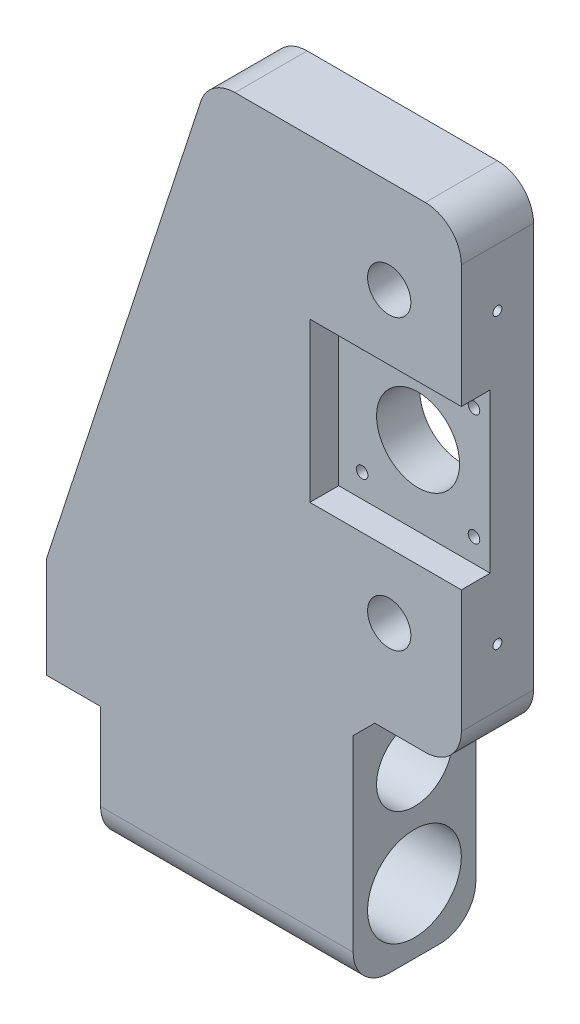
SolidWorks part; units mm, degrees
ref_plane "Front Plane" through (0, 0, 0) normal (0, 0, 1) x (1, 0, 0)
ref_plane "Top Plane" through (0, 0, 0) normal (0, 1, 0) x (1, 0, 0)
ref_plane "Right Plane" through (0, 0, 0) normal (1, 0, 0) x (0, 0, -1)
sketch "Sketch1" plane through (0, 0, 0) normal (0, 0, 1) x (1, 0, 0)
  line L0 (0, 0) -> (70, 0)
  line L1 (70, 0) -> (70, 62)
  line L2 (76, 68) -> (90, 68)
  line L3 (100, 78) -> (100, 190)
  line L4 (90, 200) -> (37.2574, 200)
  line L5 (27.7501, 193.1002) -> (-15, 62)
  line L6 (-15, 62) -> (-15, 34)
  line L7 (-15, 34) -> (0, 34)
  line L8 (0, 34) -> (0, 0)
  line L9 (70, 62) -> (76, 68)
  arc A0 (90, 68) -> (100, 78) centre (90, 78) ccw
  arc A1 (100, 190) -> (90, 200) centre (90, 190) ccw
  arc A2 (37.2574, 200) -> (27.7501, 193.1002) centre (37.2574, 190) ccw
  point P4 (70, 68)
  point P12 (100, 68)
  point P15 (100, 200)
  point P18 (30, 200)
  dimension "D8" = 10
  dimension "D1" = 70
  dimension "D2" = 200
  dimension "68" = 68
  dimension "D3" = 70
  dimension "D4" = 30
  dimension "D5" = 15
  dimension "D6" = 28
  dimension "D7" = 34
extrude "Boss-Extrude2" add sketch "Sketch1" along normal blind 34
sketch "Sketch3" plane through (0, 0, 0) normal (0, 0, -1) x (-1, 0, 0)
  line L6 (-100, 200) -> (80.4908, 200)
  line L7 (-100, 200) -> (-100, 62)
  line L8 (-100, 62) -> (80.4908, 62)
  line L9 (80.4908, 200) -> (80.4908, 62)
  line L11 (-90, 200) -> (-37.2574, 200) construction
  line L12 (-100, 78) -> (-100, 190) construction
  dimension "138" = 138
extrude "Cut-Extrude1" cut sketch "Sketch3" against normal blind 14
sketch "Sketch4" plane through (0, 0, 34) normal (0, 0, 1) x (1, 0, 0)
  line L1 (90, 200) -> (37.2574, 200) construction
  line L2 (100, 78) -> (100, 190) construction
  circle A0 centre (80, 134) radius 11.5
  circle A1 centre (95.5, 149.5) radius 1.6
  circle A2 centre (95.5, 118.5) radius 1.6
  circle A3 centre (64.5, 118.5) radius 1.6
  circle A4 centre (64.5, 149.5) radius 1.6
  circle A5 centre (80, 174) radius 6
  circle A6 centre (80, 94) radius 6
  point P17 (80, 134)
  point P19 (80, 134)
  point P20 (80, 134)
  point P21 (80, 134)
  dimension "D3" = 23
  dimension "11.58" = 11.5
  dimension "D5" = 3.2
  dimension "D7" = 12
  dimension "D10" = 15.5
  dimension "D1" = 66
  dimension "D2" = 20
  dimension "D4" = 15.5
  dimension "D8" = 40
  dimension "D9" = 80
  dimension "D6" = 4
extrude "Cut-Extrude3" cut sketch "Sketch4" against normal through all
sketch "Sketch5" plane through (0, 0, 34) normal (0, 0, 1) x (1, 0, 0)
  line L0 (100, 78) -> (100, 190) construction
  line L1 (58, 156) -> (100, 156)
  line L2 (58, 156) -> (58, 112)
  line L3 (58, 112) -> (100, 112)
  line L4 (100, 156) -> (100, 112)
  circle A0 centre (80, 134) radius 11.5 construction
  dimension "D1" = 44
  dimension "D2" = 42
  dimension "D3" = 22
extrude "Cut-Extrude4" cut sketch "Sketch5" against normal blind 8
sketch "Sketch8" plane through (100, 0, 0) normal (1, 0, 0) x (0, 0, -1)
  line L0 (-34, 200) -> (-14, 200) construction
  line L1 (-34, 174) -> (-14, 174) construction
  line L2 (-34, 156) -> (-34, 190) construction
  line L3 (-14, 190) -> (-14, 78) construction
  point P0 (-24, 174)
  point P2 (-24, 94)
  dimension "D1" = 26
  dimension "D2" = 80
hole_wizard "M3 Tapped Hole1" positions "Sketch8" profile "Sketch7" tap size "M3" standard "ISO"
sketch "Sketch7" plane through (100, 174, 24) normal (0, 1, 0) x (0, 0, -1)
  line L0 (0, 0) -> (0, 20.7511)
  line L1 (0, 20.7511) -> (1.25, 20)
  line L2 (1.25, 20) -> (1.25, 0)
  line L5 (1.25, 0) -> (0, 0)
  line L10 (0, 20.7511) -> (-1.25, 20) construction
  line L11 (0, -6.35) -> (0, 107.95) construction
  dimension "Tap Drill Dia." = 2.5
  dimension "Tap Drill Depth" = 20
  dimension "Drill Angle" = 118
cosmetic thread "Hole Thread1" parameters "D1"=6, "D2"=3
cosmetic thread "Hole Thread2" parameters "D1"=6, "D2"=3
sketch "Sketch9" plane through (70, 0, 0) normal (1, 0, 0) x (0, 0, -1)
  line L0 (-34, 0) -> (0, 0) construction
  circle A0 centre (-17, 47) radius 10.5
  circle A1 centre (-17, 18) radius 7
  dimension "D1" = 21
  dimension "D2" = 14
  dimension "D3" = 29
  dimension "D4" = 18
extrude "Cut-Extrude6" cut sketch "Sketch9" against normal through all
sketch "Sketch10" plane through (0, 0, 0) normal (-1, 0, 0) x (0, 0, 1)
  circle A0 centre (17, 18) radius 11.5
  dimension "D1" = 23
extrude "Cut-Extrude7" cut sketch "Sketch10" against normal blind 6
sketch "Sketch11" plane through (70, 0, 0) normal (1, 0, 0) x (0, 0, -1)
  circle A0 centre (-17, 18) radius 13
  dimension "D1" = 26
extrude "Cut-Extrude8" cut sketch "Sketch11" against normal blind 34
chamfer "Chamfer1" distance 6 angle 45 2 edges at (27.5, 62, 0) (27.5, 62, 14)
fillet "Fillet1" radius 10 2 edges at (35, 0, 0) (35, 0, 34)
sketch "Sketch12" plane through (6, 0, 0) normal (-1, 0, 0) x (0, 0, 1)
  line L0 (17, 18) -> (17, 26) construction
  line L1 (17, 18) -> (25, 18) construction
  line L2 (17, 18) -> (17, 10) construction
  line L3 (17, 18) -> (9, 18) construction
  circle A0 centre (17, 26) radius 1.5
  circle A1 centre (17, 18) radius 7 construction
  circle A2 centre (25, 18) radius 1.5
  circle A3 centre (17, 10) radius 1.5
  circle A4 centre (9, 18) radius 1.5
  point P15 (17, 18)
  dimension "D1" = 3
  dimension "D2" = 8
  dimension "D3" = 4
extrude "Cut-Extrude9" cut sketch "Sketch12" against normal up to surface (30 mm away) up to face at (36, 18, 4)
sketch "Sketch13" plane through (0, 0, 14) normal (0, 0, -1) x (-1, 0, 0)
  circle A0 centre (-95.5, 149.5) radius 2.75
  circle A1 centre (-64.5, 149.5) radius 2.75
  circle A2 centre (-64.5, 118.5) radius 2.75
  circle A3 centre (-95.5, 118.5) radius 2.75
  point P12 (-80, 134)
  dimension "D1" = 5.5
  dimension "D2" = 4
extrude "Cut-Extrude10" cut sketch "Sketch13" against normal blind 3.5
